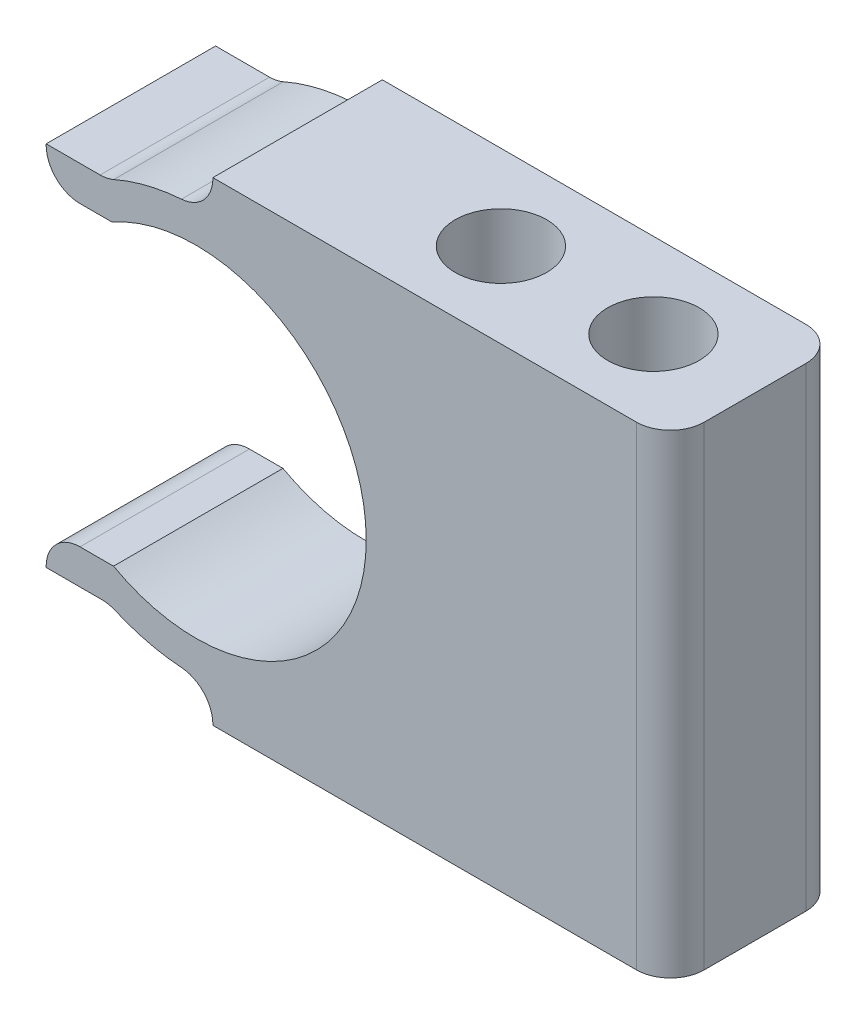
SolidWorks part; units mm, degrees
ref_plane "Front Plane" through (0, 0, 0) normal (0, 0, 1) x (1, 0, 0)
ref_plane "Top Plane" through (0, 0, 0) normal (0, 1, 0) x (1, 0, 0)
ref_plane "Right Plane" through (0, 0, 0) normal (1, 0, 0) x (0, 0, -1)
sketch "Sketch1" plane through (0, 0, 0) normal (0, 0, 1) x (1, 0, 0)
  line L0 (0, 0) -> (28, 0) construction
  line L2 (1, -11.9583) -> (1, -14)
  line L3 (6, 14) -> (28, 14)
  line L5 (10, -14) -> (28, -14)
  line L6 (28, 14) -> (28, -14)
  line L7 (6, 14) -> (1, 14)
  line L9 (10, -14) -> (1, -14)
  line L10 (1, 14) -> (1, 11.9583)
  line L11 (-8.8412, 0) -> (-10, 0) construction
  line L12 (-8.8412, 8.75) -> (-4.9437, 8.75)
  line L13 (-8.8412, 8.75) -> (-8.8412, -8.75) construction
  line L14 (-8.8412, -8.7938) -> (-4.8654, -8.7938)
  line L19 (-5.2173, 10.8065) -> (-8.8412, 10.8065)
  line L20 (-8.8412, 8.75) -> (-8.8412, 10.8065)
  line L23 (-5.1278, -10.8492) -> (-8.8412, -10.8492)
  line L24 (-8.8412, -8.7938) -> (-8.8412, -10.8492)
  arc A0 (-4.8654, -8.7938) -> (-4.9437, 8.75) centre (0, 0) ccw
  arc A1 (1, 11.9583) -> (-5.2173, 10.8065) centre (0, 0) ccw
  arc A2 (-5.1278, -10.8492) -> (1, -11.9583) centre (0, 0) ccw
  point P22 (-8.8412, 0)
  dimension "D1" = 20.1
  dimension "D2" = 24
  dimension "D3" = 28
  dimension "D4" = 28
  dimension "D5" = 18
  dimension "D6" = 9
  dimension "D7" = 17.5
extrude "Boss-Extrude1" add sketch "Sketch1" along normal blind 10
fillet "Fillet1" radius 2 8 edges at (1, -11.9583, 5) (1, 11.9583, 5) (-5.1278, -10.8492, 5) (-8.8412, 8.75, 5) (-8.8412, -8.7938, 5) (-5.2173, 10.8065, 5) (28, 0, 0) (28, 0, 10)
sketch "Sketch2" plane through (0, -14, 0) normal (0, -1, 0) x (1, 0, 0)
  line L0 (22, 5) -> (28, 5) construction
  line L1 (22, 5) -> (13, 5) construction
  line L2 (28, 8) -> (28, 2) construction
  line L3 (13, 5) -> (0, 5) construction
  line L6 (0, 5) -> (0, 0) construction
  circle A0 centre (13, 5) radius 2.7
  circle A1 centre (22, 5) radius 2.7
  point P7 (28, 5)
  dimension "D1" = 5.4
  dimension "D2" = 9
  dimension "D3" = 13
extrude "Cut-Extrude1" cut sketch "Sketch2" against normal through all
